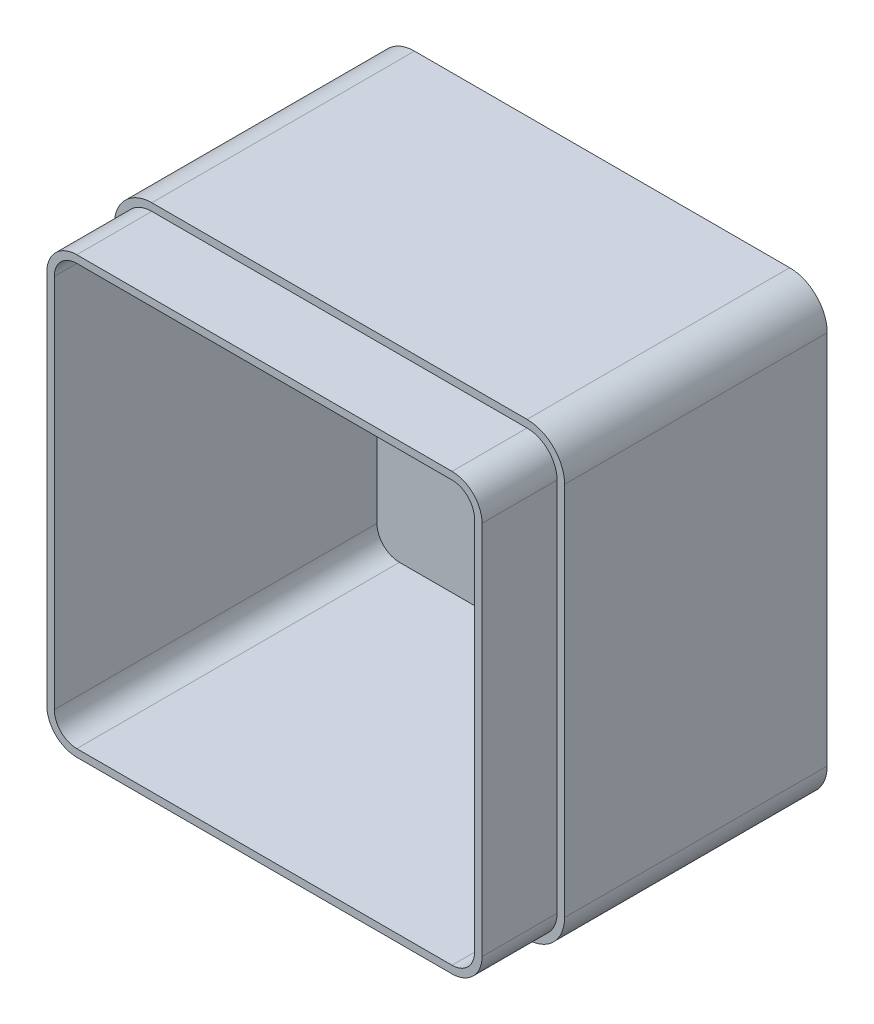
SolidWorks part; units mm, degrees
ref_plane "Front Plane" through (0, 0, 0) normal (0, 0, 1) x (1, 0, 0)
ref_plane "Top Plane" through (0, 0, 0) normal (0, 1, 0) x (1, 0, 0)
ref_plane "Right Plane" through (0, 0, 0) normal (1, 0, 0) x (0, 0, -1)
sketch "Sketch1" plane through (0, 0, 0) normal (0, 0, 1) x (1, 0, 0)
  line L1 (0, 0) -> (120, 0)
  line L2 (0, 0) -> (0, 120)
  line L3 (0, 120) -> (120, 120)
  line L4 (120, 0) -> (120, 120)
  dimension "D1" = 120
  dimension "D2" = 120
extrude "Boss-Extrude1" add sketch "Sketch1" along normal blind 90
fillet "Fillet1" radius 10 4 edges at (0, 0, 45) (0, 120, 45) (120, 0, 45) (120, 120, 45)
shell "Shell2" thickness 4
sketch "Sketch4" plane through (0, 0, 90) normal (0, 0, 1) x (1, 0, 0)
  line L0 (2, 110) -> (2, 10)
  line L1 (10, 2) -> (110, 2)
  line L2 (118, 10) -> (118, 110)
  line L3 (110, 118) -> (10, 118)
  line L4 (0, 110) -> (0, 10)
  line L5 (10, 0) -> (110, 0)
  line L6 (120, 10) -> (120, 110)
  line L7 (110, 120) -> (10, 120)
  line L8 (0, 110) -> (0, 10)
  line L9 (10, 0) -> (110, 0)
  line L10 (120, 10) -> (120, 110)
  line L11 (110, 120) -> (10, 120)
  arc A0 (2, 10) -> (10, 2) centre (10, 10) ccw
  arc A1 (110, 2) -> (118, 10) centre (110, 10) ccw
  arc A2 (118, 110) -> (110, 118) centre (110, 110) ccw
  arc A3 (10, 118) -> (2, 110) centre (10, 110) ccw
  arc A4 (0, 10) -> (10, 0) centre (10, 10) ccw
  arc A5 (110, 0) -> (120, 10) centre (110, 10) ccw
  arc A6 (120, 110) -> (110, 120) centre (110, 110) ccw
  arc A7 (10, 120) -> (0, 110) centre (10, 110) ccw
  arc A8 (0, 10) -> (10, 0) centre (10, 10) ccw
  arc A9 (110, 0) -> (120, 10) centre (110, 10) ccw
  arc A10 (120, 110) -> (110, 120) centre (110, 110) ccw
  arc A11 (10, 120) -> (0, 110) centre (10, 110) ccw
  dimension "D1" = 0
  dimension "D2" = 2
extrude "Cut-Extrude13" cut sketch "Sketch4" against normal blind 20
